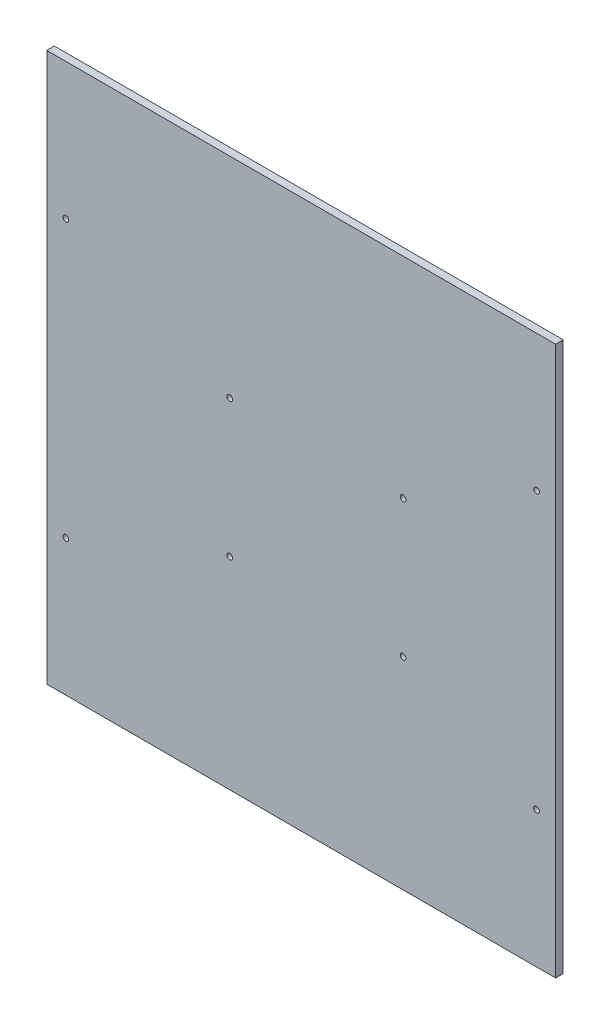
SolidWorks part; units mm, degrees
ref_plane "Plan de face" through (0, 0, 0) normal (0, 0, 1) x (1, 0, 0)
ref_plane "Plan de dessus" through (0, 0, 0) normal (0, 1, 0) x (1, 0, 0)
ref_plane "Plan de droite" through (0, 0, 0) normal (1, 0, 0) x (0, 0, -1)
sketch "Esquisse1" plane through (0, 0, 0) normal (0, 0, 1) x (1, 0, 0)
  line L0 (0, 182.1442) -> (0, 37.1442) construction
  line L1 (-10, 253.6442) -> (257, 253.6442)
  line L2 (-10, 253.6442) -> (-10, -34.3558)
  line L3 (-10, -34.3558) -> (257, -34.3558)
  line L4 (257, 253.6442) -> (257, -34.3558)
  line L5 (247, 182.1442) -> (247, 37.1442) construction
  circle A0 centre (0, 182.1442) radius 1.5
  circle A1 centre (0, 37.1442) radius 1.5
  circle A2 centre (247, 37.1442) radius 1.5
  circle A3 centre (247, 182.1442) radius 1.5
  dimension "D1" = 288
  dimension "D2" = 267
  dimension "D3" = 71.5
  dimension "D4" = 71.5
  dimension "D5" = 71.5
  dimension "D6" = 71.5
  dimension "D7" = 10
  dimension "D8" = 10
extrude "Extrusion1" add sketch "Esquisse1" along normal blind 4
sketch "Esquisse2" plane through (0, 0, 4) normal (0, 0, 1) x (1, 0, 0)
  line L0 (257, 253.6442) -> (-10, 253.6442) construction
  line L1 (86, 143.6442) -> (177, 143.6442) construction
  line L2 (86, 143.6442) -> (86, 71.6442) construction
  line L3 (86, 71.6442) -> (177, 71.6442) construction
  line L4 (177, 143.6442) -> (177, 71.6442) construction
  line L5 (257, -34.3558) -> (257, 253.6442) construction
  circle A0 centre (86, 143.6442) radius 1.5
  circle A1 centre (177, 143.6442) radius 1.5
  circle A2 centre (177, 71.6442) radius 1.5
  circle A3 centre (86, 71.6442) radius 1.5
  dimension "D3" = 110
  dimension "D1" = 91
  dimension "D2" = 72
  dimension "D4" = 80
extrude "Extrusion2" cut sketch "Esquisse2" against normal blind 10
